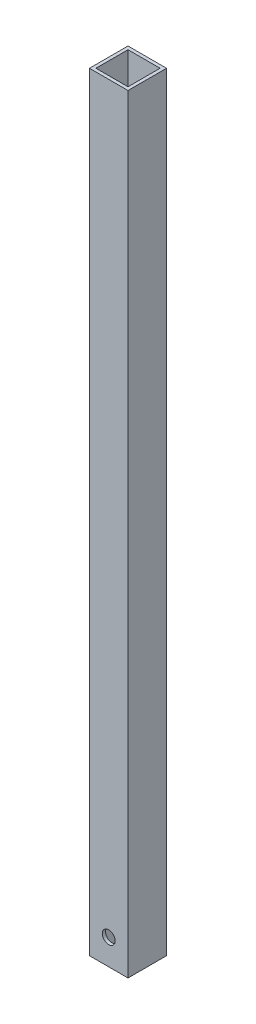
SolidWorks part; units mm, degrees
ref_plane "Front Plane" through (0, 0, 0) normal (0, 0, 1) x (1, 0, 0)
ref_plane "Top Plane" through (0, 0, 0) normal (0, 1, 0) x (1, 0, 0)
ref_plane "Right Plane" through (0, 0, 0) normal (1, 0, 0) x (0, 0, -1)
sketch "Sketch1" plane through (0, 0, 0) normal (0, 1, 0) x (1, 0, 0)
  line L1 (-7.9375, -7.9375) -> (7.9375, -7.9375)
  line L2 (-7.9375, -7.9375) -> (-7.9375, 7.9375)
  line L3 (-7.9375, 7.9375) -> (7.9375, 7.9375)
  line L4 (7.9375, -7.9375) -> (7.9375, 7.9375)
  line L5 (-7.9375, -7.9375) -> (7.9375, 7.9375) construction
  line L6 (-7.9375, 7.9375) -> (7.9375, -7.9375) construction
  line L7 (-9.525, -9.525) -> (9.525, -9.525)
  line L8 (-9.525, -9.525) -> (-9.525, 9.525)
  line L9 (-9.525, 9.525) -> (9.525, 9.525)
  line L10 (9.525, -9.525) -> (9.525, 9.525)
  line L11 (-9.525, -9.525) -> (9.525, 9.525) construction
  line L12 (-9.525, 9.525) -> (9.525, -9.525) construction
  point P0 (0, 0)
  point P6 (0, 0)
  dimension "D1" = 19.05
  dimension "D2" = 1.5875
extrude "Boss-Extrude1" add sketch "Sketch1" along normal blind 380
sketch "Sketch2" plane through (0, 0, 9.525) normal (0, 0, 1) x (1, 0, 0)
  circle A0 centre (0, 12.7) radius 3.175
  dimension "D1" = 6.35
  dimension "D2" = 12.7
extrude "Cut-Extrude1" cut sketch "Sketch2" against normal through all
